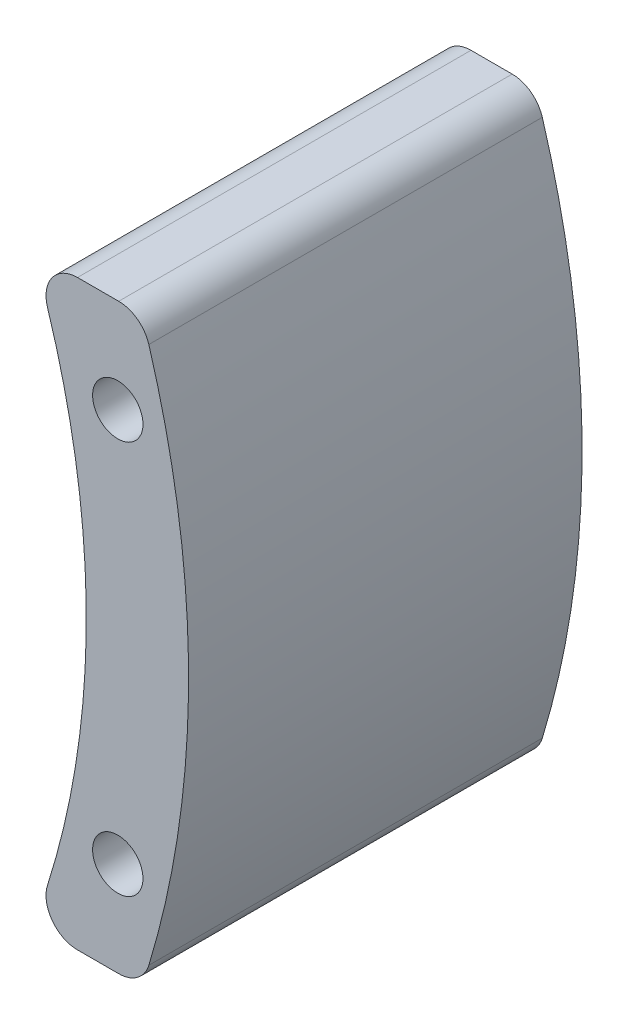
SolidWorks part; units mm, degrees
ref_plane "Front Plane" through (0, 0, 0) normal (1, 0, 0) x (0, 1, 0)
ref_plane "Top Plane" through (0, 0, 0) normal (0, 0, 1) x (0, 1, 0)
ref_plane "Right Plane" through (0, 0, 0) normal (0, 1, 0) x (-1, 0, 0)
sketch "Sketch1" plane through (0, 0, 0) normal (0, 0, 1) x (0, 1, 0)
  line L0 (-18.5, -51.9423) -> (-18.5, -54.5596)
  line L1 (18.5, -54.5596) -> (18.5, -51.9423)
  line L2 (0, 0) -> (0, 50000) construction
  line L3 (-14.06, -59) -> (49985.94, -59) construction
  arc A0 (-15.8945, -50.0361) -> (15.8945, -50.0361) centre (0, 0) ccw
  arc A1 (-17.0789, -56.474) -> (17.0789, -56.474) centre (0, 0) ccw
  arc A2 (-15.8945, -50.0361) -> (-18.5, -51.9423) centre (-16.5, -51.9423) ccw
  arc A3 (-17.0789, -56.474) -> (-18.5, -54.5596) centre (-16.5, -54.5596) cw
  arc A4 (17.0789, -56.474) -> (18.5, -54.5596) centre (16.5, -54.5596) ccw
  arc A5 (15.8945, -50.0361) -> (18.5, -51.9423) centre (16.5, -51.9423) cw
  circle A6 centre (-12.5, -54.5) radius 1.6
  circle A7 centre (12.5, -54.5) radius 1.6
  point P19 (0, 0)
  dimension "D1" = 52.5
  dimension "D2" = 59
  dimension "D4" = 2
  dimension "D5" = 3.2
  dimension "D3" = 37
  dimension "D6" = 4.5
  dimension "D7" = 25
extrude "Boss-Extrude1" add sketch "Sketch1" along normal blind 25
equation "\"D2@Sketch1\"=118/2"
